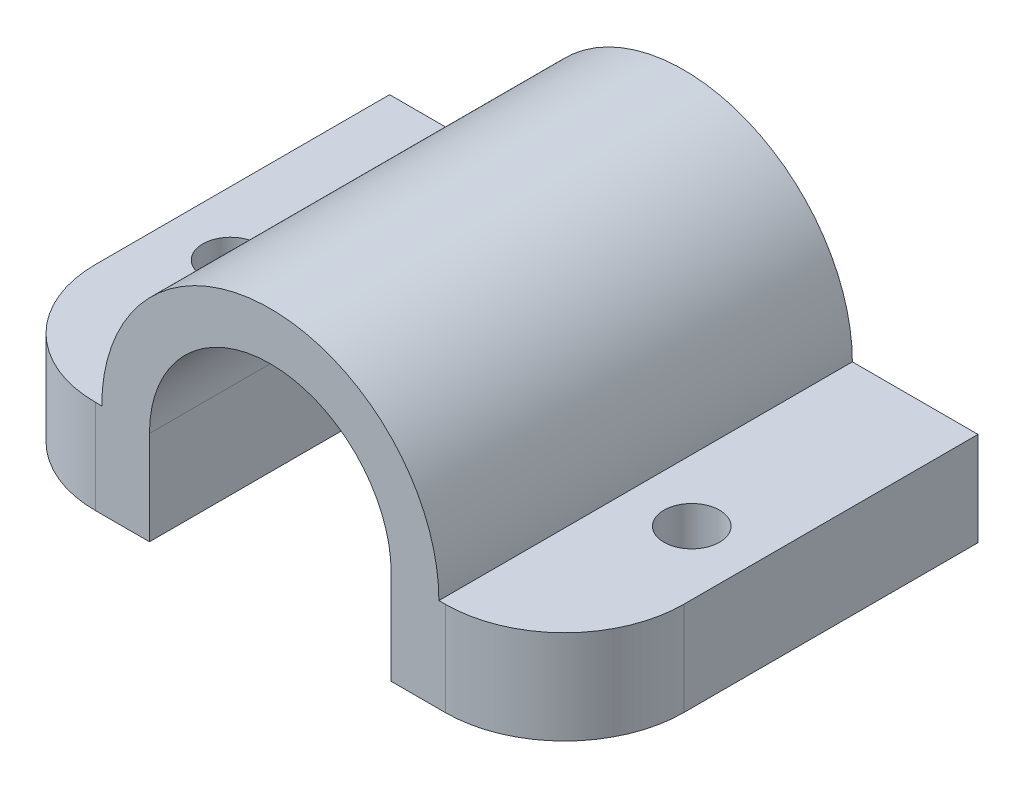
SolidWorks part; units mm, degrees
ref_plane "Płaszczyzna przednia" through (0, 0, 0) normal (0, 0, 1) x (1, 0, 0)
ref_plane "Płaszczyzna górna" through (0, 0, 0) normal (0, 1, 0) x (1, 0, 0)
ref_plane "Płaszczyzna prawa" through (0, 0, 0) normal (1, 0, 0) x (0, 0, -1)
sketch "Szkic1" plane through (0, 0, 0) normal (0, 0, 1) x (1, 0, 0)
  line L0 (7.6, -5.9) -> (-7.6, -5.9)
  line L1 (0, 0) -> (14.5, 0) construction
  line L2 (0, 0) -> (-14.5, 0) construction
  line L3 (-7.6, -5.9) -> (-14.5, -5.9) construction
  line L4 (-14.5, -5.9) -> (-14.5, 0) construction
  line L5 (14.5, 0) -> (14.5, -5.9) construction
  line L6 (14.5, -5.9) -> (7.6, -5.9) construction
  line L7 (-7.6, 0) -> (-7.6, -5.9)
  line L8 (7.6, 0) -> (7.6, -5.9)
  line L9 (-7.6, -5.9) -> (-18.5, -5.9)
  line L10 (7.6, -5.9) -> (18.5, -5.9)
  line L11 (0, 0) -> (0, -5.9) construction
  line L12 (-18.5, -5.9) -> (-18.5, 0)
  line L13 (-18.5, 0) -> (-10.6, 0)
  line L14 (10.6, 0) -> (18.5, 0)
  line L15 (18.5, 0) -> (18.5, -5.9)
  arc A0 (7.6, 0) -> (-7.6, 0) centre (0, 0) ccw
  arc A1 (-10.6, 0) -> (10.6, 0) centre (0, 0) cw
  point P5 (0, 7.6)
  point P18 (0, 0)
  dimension "D1" = 15.2
  dimension "D5" = 3
  dimension "D2" = 13.5
  dimension "D3" = 29
  dimension "D4" = 4
extrude "Dodanie-wyciągnięcie1" add sketch "Szkic1" along normal mid plane 24 contours A1 L13 L12 L9 L7 A0 L8 L10 L15 L14
sketch "Szkic2" plane through (0, 0, -12) normal (0, 0, -1) x (-1, 0, 0)
  line L0 (7.6, 0) -> (7.6, -5.9) construction
  line L1 (-7.6, 0) -> (-7.6, -5.9) construction
  line L2 (7.6, 0) -> (7.6, -5.9)
  line L3 (-7.6, 0) -> (-7.6, -5.9)
  line L4 (-4.6, 0) -> (-4.6, -5.9)
  line L5 (4.6, 0) -> (4.6, -5.9)
  line L6 (-7.6, -5.9) -> (-4.6, -5.9)
  line L7 (7.6, -5.9) -> (4.6, -5.9)
  line L16 (-10.6, 0) -> (-18.5, 0)
  line L17 (-18.5, 0) -> (-18.5, -5.9)
  line L18 (-18.5, -5.9) -> (-7.6, -5.9)
  line L19 (-7.6, -5.9) -> (-7.6, 0)
  line L20 (7.6, 0) -> (7.6, -5.9)
  line L21 (7.6, -5.9) -> (18.5, -5.9)
  line L22 (18.5, -5.9) -> (18.5, 0)
  line L23 (18.5, 0) -> (10.6, 0)
  line L24 (-10.6, 0) -> (-18.5, 0)
  line L25 (-18.5, 0) -> (-18.5, -5.9)
  line L26 (-18.5, -5.9) -> (-7.6, -5.9)
  line L27 (-7.6, -5.9) -> (-7.6, 0)
  line L28 (7.6, 0) -> (7.6, -5.9)
  line L29 (7.6, -5.9) -> (18.5, -5.9)
  line L30 (18.5, -5.9) -> (18.5, 0)
  line L31 (18.5, 0) -> (10.6, 0)
  arc A0 (7.6, 0) -> (-7.6, 0) centre (0, 0) ccw construction
  arc A1 (7.6, 0) -> (-7.6, 0) centre (0, 0) ccw
  arc A2 (4.6, 0) -> (-4.6, 0) centre (0, 0) ccw
  arc A5 (10.6, 0) -> (-10.6, 0) centre (0, 0) ccw
  arc A6 (7.6, 0) -> (-7.6, 0) centre (0, 0) ccw
  arc A7 (10.6, 0) -> (-10.6, 0) centre (0, 0) ccw
  arc A8 (7.6, 0) -> (-7.6, 0) centre (0, 0) ccw
  arc M19 (10.6, 0) -> (-10.6, 0) centre (0, 0) ccw
  line M20 (-10.6, 0) -> (-18.5, 0)
  line M21 (-18.5, 0) -> (-18.5, -5.9)
  line M22 (-18.5, -5.9) -> (-7.6, -5.9)
  line M23 (-7.6, -5.9) -> (-7.6, 0)
  arc M24 (-7.6, 0) -> (7.6, 0) centre (0, 0) cw
  line M25 (7.6, 0) -> (7.6, -5.9)
  line M26 (7.6, -5.9) -> (18.5, -5.9)
  line M27 (18.5, -5.9) -> (18.5, 0)
  line M28 (18.5, 0) -> (10.6, 0)
  dimension "D1" = 3
  dimension "D2" = 0
extrude "Dodanie-wyciągnięcie2" add sketch "Szkic2" along normal blind 2 contours M28 M19 M20 M21 M22 M23 M24 M25 M26 M27 | A2 L5 L7 L6 L4 M25 M24 M23
sketch "Szkic3" plane through (0, 0, 0) normal (0, 1, 0) x (1, 0, 0)
  circle A0 centre (-14.5, 0) radius 1.75
  circle A1 centre (14.5, 0) radius 1.75
  point P4 (0, 0)
  point P6 (0, 0)
  dimension "D1" = 3.5
extrude "Wytnij-wyciągnięcie1" cut sketch "Szkic3" against normal up to next
fillet "Zaokrąglenie1" radius 7.5 2 edges at (18.5, -2.95, 12) (-18.5, -2.95, 12)
